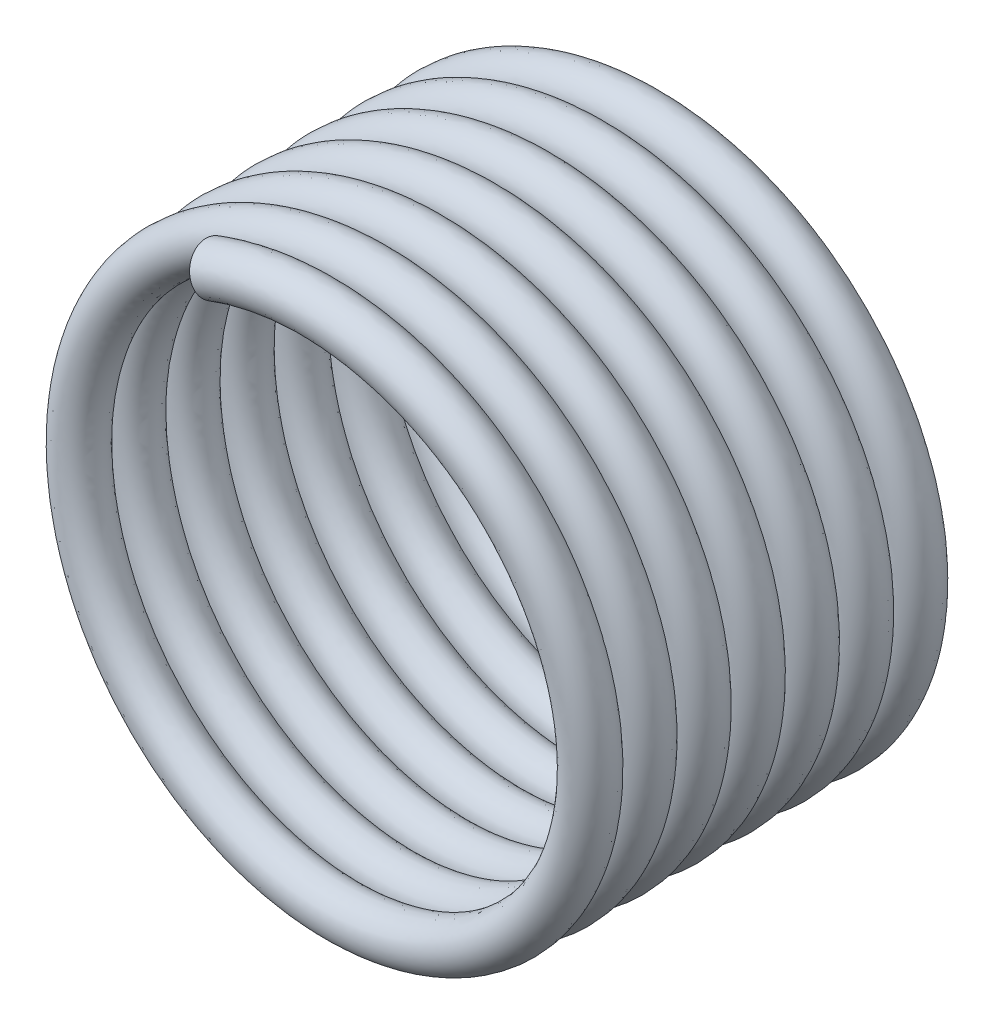
SolidWorks part; units mm, degrees
ref_plane "Front Plane" through (0, 0, 0) normal (0, 0, 1) x (1, 0, 0)
ref_plane "Top Plane" through (0, 0, 0) normal (0, 1, 0) x (1, 0, 0)
ref_plane "Right Plane" through (0, 0, 0) normal (1, 0, 0) x (0, 0, -1)
sketch "Sketch1" plane through (0, 0, 0) normal (0, 0, 1) x (1, 0, 0)
  circle A0 centre (0, 0) radius 5.3721
  dimension "D1" = 10.7442
curve "Helix/Spiral1" pitch 1.1235 height 7.6454 turns 6.805
ref_plane "Plane1" through (-1.8197, 5.0545, 7.6454) normal (-0.9404, -0.3386, 0.0333) x (0.037, -0.0047, 0.9993)
sketch "Sketch2" plane through (-1.8197, 5.0545, 7.6454) normal (-0.9404, -0.3386, 0.0333) x (0.037, -0.0047, 0.9993)
  circle A0 centre (0.0016, 0.2066) radius 0.4826
  dimension "D1" = 0.9652
sweep "Sweep1" add profiles "Sketch2" path "Helix/Spiral1"
sketch "Sketch3" plane through (-1.8197, 5.0545, 7.6454) normal (-0.9404, -0.3386, 0.0333) x (0.037, -0.0047, 0.9993)
  circle A1 centre (0.0016, 0.2066) radius 0.4826
extrude "Boss-Extrude1" [suppressed] add sketch "Sketch3" along normal blind 31.75
sketch "Sketch4" plane through (0, 0, 0) normal (0, 0.9994, -0.0333) x (1, 0, 0)
  circle A0 centre (-5.5787, -0.0051) radius 0.4826
  circle A1 centre (-5.5787, -0.0051) radius 0.4826 construction
extrude "Boss-Extrude2" [suppressed] add sketch "Sketch4" along normal blind 31.75
